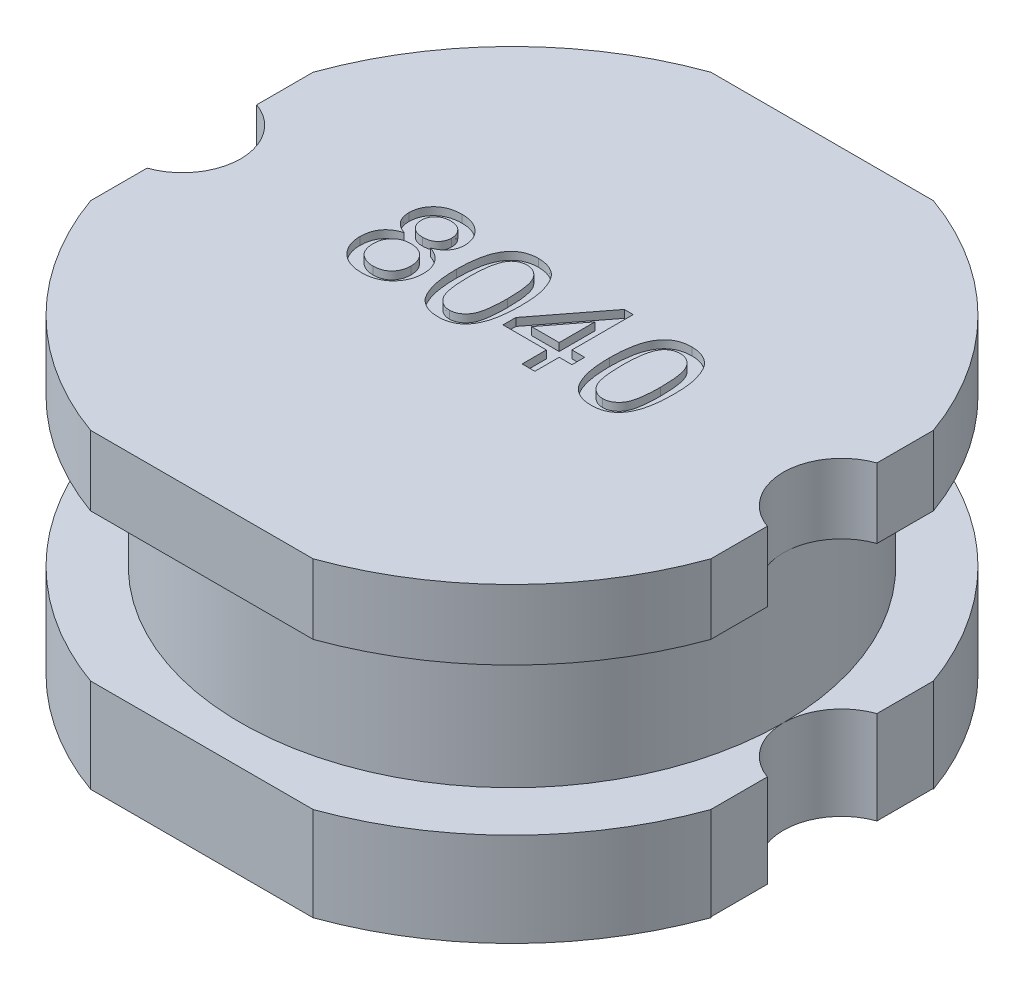
SolidWorks part; units mm, degrees
ref_plane "Спереди" through (0, 0, 0) normal (0, 0, 1) x (1, 0, 0)
ref_plane "Сверху" through (0, 0, 0) normal (0, 1, 0) x (1, 0, 0)
ref_plane "Справа" through (0, 0, 0) normal (1, 0, 0) x (0, 0, -1)
sketch "Эскиз1" plane through (0, 0, 0) normal (0, 1, 0) x (1, 0, 0)
  line L0 (4, 0) -> (-4, 0) construction
  line L1 (-1.4361, 4) -> (1.4361, 4)
  line L2 (-4, 1.4361) -> (-4, 0.7071)
  line L3 (-1.4361, -4) -> (1.4361, -4)
  line L4 (4, 1.4361) -> (4, 0.7071)
  line L5 (-4, -0.7071) -> (-4, -1.4361)
  line L6 (4, -0.7071) -> (4, -1.4361)
  arc A0 (-4, -1.4361) -> (-1.4361, -4) centre (0, 0) ccw
  arc A1 (1.4361, -4) -> (4, -1.4361) centre (0, 0) ccw
  arc A2 (4, 1.4361) -> (1.4361, 4) centre (0, 0) ccw
  arc A3 (-1.4361, 4) -> (-4, 1.4361) centre (0, 0) ccw
  arc A4 (-4, -0.7071) -> (-4, 0.7071) centre (-4.25, 0) ccw
  arc A5 (4, 0.7071) -> (4, -0.7071) centre (4.25, 0) ccw
  dimension "D5" = 8.5
  dimension "D6" = 1.5
  dimension "D7" = 1.5
  dimension "D1" = 8
  dimension "D2" = 8
  dimension "D3" = 4
  dimension "D4" = 4
  dimension "D8" = 4.25
  dimension "D9" = 4.25
extrude "Бобышка-Вытянуть1" add sketch "Эскиз1" along normal blind 4
sketch "Эскиз2" plane through (0, 0, 0) normal (1, 0, 0) x (0, 0, -1)
  line L0 (0, 0) -> (0, 4) construction
  line L1 (-1.4361, 4) -> (-4, 4) construction
  line L2 (-4.25, 3.1) -> (-3.5, 3.1)
  line L3 (-4.25, 3.1) -> (-4.25, 1.2)
  line L4 (-4.25, 1.2) -> (-3.5, 1.2)
  line L5 (-3.5, 3.1) -> (-3.5, 1.2)
  line L6 (-4, 0) -> (-1.4361, 0) construction
  dimension "D1" = 0.9
  dimension "D2" = 1.2
  dimension "D3" = 0.75
  dimension "D4" = 4.25
revolve "Вырез-Повернуть1" cut sketch "Эскиз2" angle 360 about L0
sketch "Эскиз3" plane through (0, 0, 0) normal (0, -1, 0) x (1, 0, 0)
  line L0 (-4, 1.4361) -> (4, 1.4361)
  line L1 (-1.4361, 4) -> (1.4361, 4)
  line L2 (-4.7139, 0) -> (5.3766, 0) construction
  line L3 (-1.4361, -4) -> (1.4361, -4)
  line L4 (-4, -1.4361) -> (4, -1.4361)
  arc A0 (-1.4361, 4) -> (-4, 1.4361) centre (0, 0) ccw
  arc A1 (4, 1.4361) -> (1.4361, 4) centre (0, 0) ccw
  arc A2 (4, -1.4361) -> (1.4361, -4) centre (0, 0) cw
  arc A3 (-1.4361, -4) -> (-4, -1.4361) centre (0, 0) cw
extrude "Бобышка-Вытянуть2" add sketch "Эскиз3" along normal blind 0.01
sketch "Эскиз4" plane through (0, 4, 0) normal (0, 1, 0) x (1, 0, 0)
  text T0 "8040" font "Arial" height in points 5
extrude "Вырез-Вытянуть1" cut sketch "Эскиз4" against normal blind 0.1
